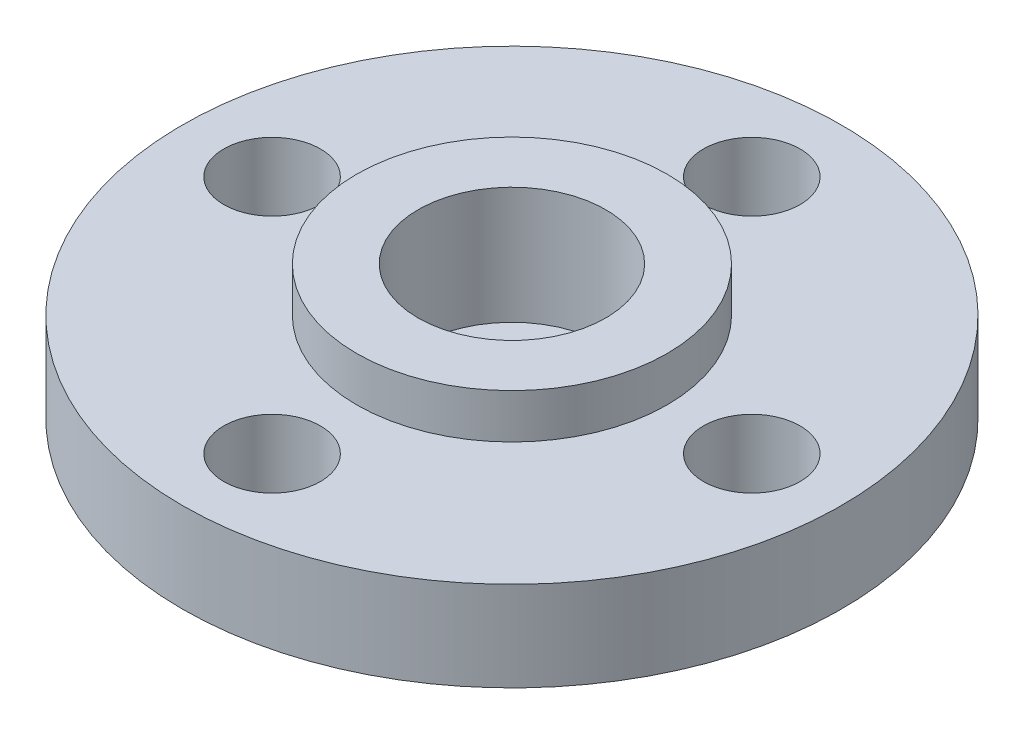
SolidWorks part; units mm, degrees
ref_plane "Front" through (0, 0, 0) normal (0, 0, 1) x (1, 0, 0)
ref_plane "Top" through (0, 0, 0) normal (0, 1, 0) x (1, 0, 0)
ref_plane "Right" through (0, 0, 0) normal (1, 0, 0) x (0, 0, -1)
sketch "Sketch1" plane through (0, 0, 0) normal (0, 1, 0) x (1, 0, 0)
  circle A0 centre (0, 0) radius 9.55
  dimension "D1" = 19.1
extrude "Boss-Extrude1" add sketch "Sketch1" along normal blind 2.6
sketch "Sketch2" plane through (0, 2.6, 0) normal (0, 1, 0) x (1, 0, 0)
  circle A0 centre (0, 0) radius 4.5
  dimension "D1" = 9
extrude "Boss-Extrude2" add sketch "Sketch2" along normal blind 1.29
sketch "Sketch3" plane through (0, 3.89, 0) normal (0, 1, 0) x (1, 0, 0)
  circle A0 centre (0, 0) radius 2.72
  dimension "D1" = 5.44
extrude "Cut-Extrude1" cut sketch "Sketch3" against normal offset from surface 0.5 and the other way through all up to face at (0, 0, 9.55)
sketch "Sketch4" plane through (0, 2.6, 0) normal (0, 1, 0) x (1, 0, 0)
  line L0 (0, -2.1395) -> (0, 2.1395) construction
  line L1 (0, 6.95) -> (0, -6.95) construction
  line L2 (-2.1395, 0) -> (2.1395, 0) construction
  circle A0 centre (0, 6.95) radius 1.4
  circle A1 centre (6.95, 0) radius 1.4
  circle A2 centre (0, -6.95) radius 1.4
  circle A3 centre (-6.95, 0) radius 1.4
  point P6 (-6.95, 0)
  point P13 (0, 0)
  point P14 (-6.95, 0)
  dimension "D1" = 2.8
  dimension "D3" = 13.9
  dimension "D2" = 4
extrude "Cut-Extrude2" cut sketch "Sketch4" against normal through all
